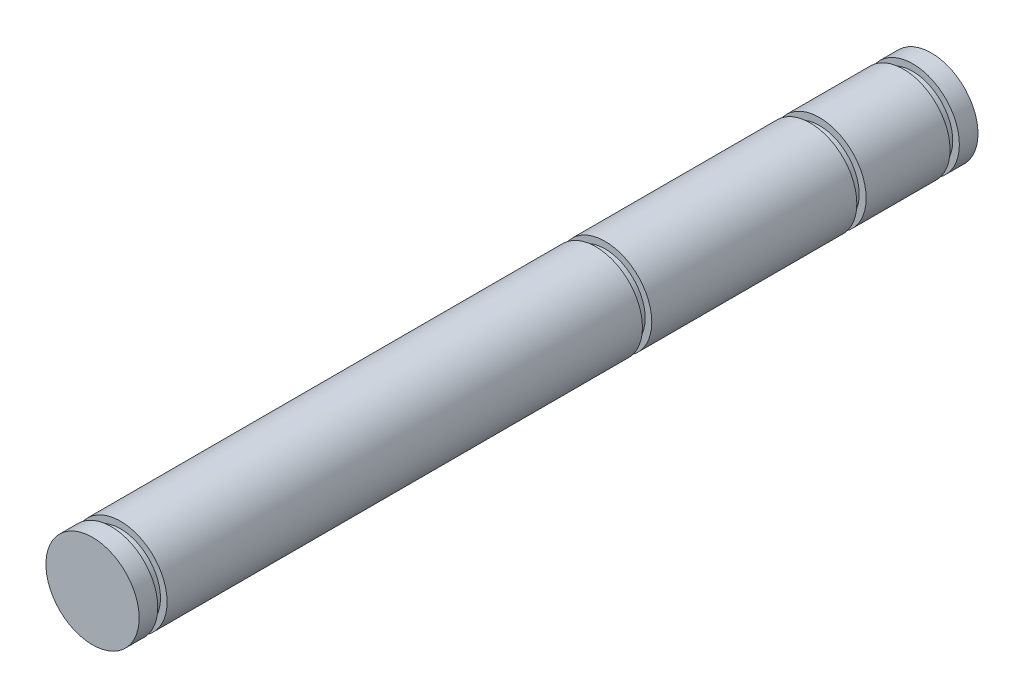
SolidWorks part; units mm, degrees
ref_plane "Vorne" through (0, 0, 0) normal (0, 0, 1) x (1, 0, 0)
ref_plane "Oben" through (0, 0, 0) normal (0, 1, 0) x (1, 0, 0)
ref_plane "Rechts" through (0, 0, 0) normal (1, 0, 0) x (0, 0, -1)
ref_plane "E_Boden" through (0, 1, 0) normal (0, 1, 0) x (1, 0, 0)
sketch "Skizze1" plane through (0, 0, 0) normal (1, 0, 0) x (0, 0, -1)
  line L0 (-17.9236, 0) -> (92.5153, 0) construction
  line L1 (-7.3158, 0) -> (-7.3158, 5)
  line L2 (-7.3158, 5) -> (-5.3158, 5)
  line L3 (-5.3158, 5) -> (-5.3158, 4.292)
  line L4 (-5.3158, 4.292) -> (-4.3158, 4.292)
  line L5 (-4.3158, 4.292) -> (-4.3158, 5)
  line L6 (-4.3158, 5) -> (46.6842, 5)
  line L7 (46.6842, 5) -> (46.6842, 4.292)
  line L8 (46.6842, 4.292) -> (47.6842, 4.292)
  line L9 (47.6842, 4.292) -> (47.6842, 5)
  line L10 (47.6842, 5) -> (69.6842, 5)
  line L11 (69.6842, 5) -> (69.6842, 4.2559)
  line L12 (69.6842, 4.2559) -> (70.6842, 4.2559)
  line L13 (70.6842, 4.2559) -> (70.6842, 5)
  line L14 (70.6842, 5) -> (79.6842, 5)
  line L15 (79.6842, 5) -> (79.6842, 4.292)
  line L16 (79.6842, 4.292) -> (80.6842, 4.292)
  line L17 (80.6842, 4.292) -> (80.6842, 5)
  line L18 (80.6842, 5) -> (82.6842, 5)
  line L19 (82.6842, 5) -> (82.6842, 0)
  line L20 (-7.3158, 0) -> (82.6842, 0)
  dimension "D1" = 5
  dimension "D2" = 2
  dimension "D3" = 1
  dimension "D4" = 51
  dimension "D5" = 1
  dimension "D6" = 9
  dimension "D7" = 1
  dimension "D8" = 22
  dimension "D9" = 1
  dimension "D10" = 2
  dimension "D11" = 5
  dimension "D12" = 5
  dimension "D13" = 5
revolve "Rotation1" add sketch "Skizze1" angle 360 about L20
